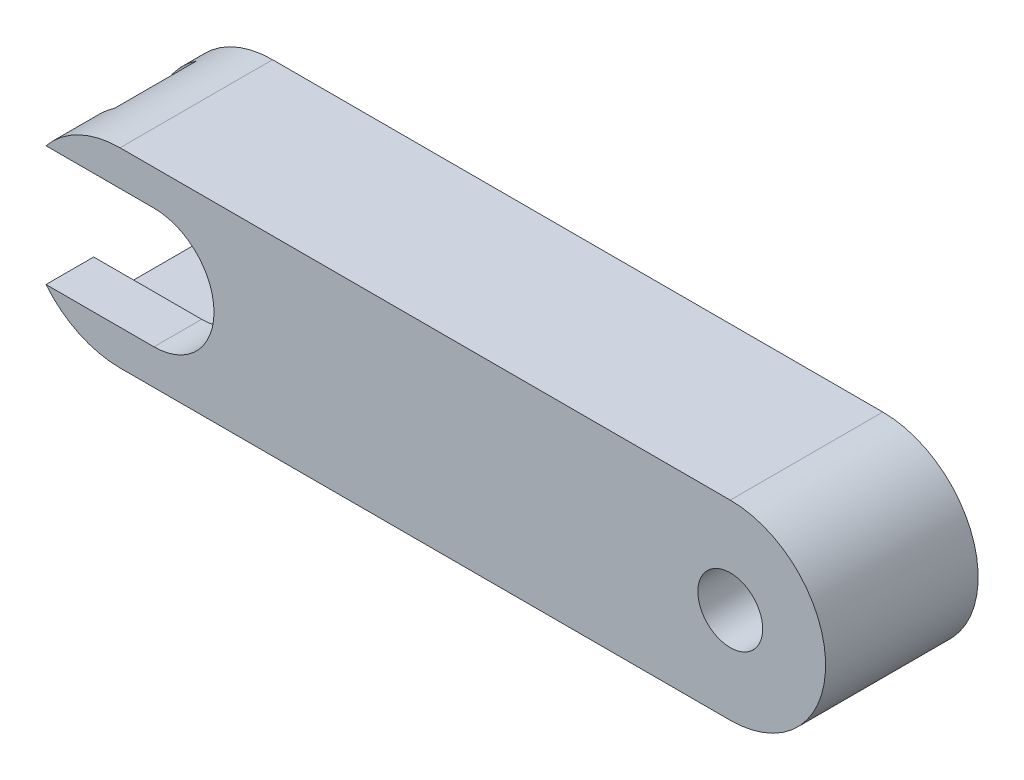
SolidWorks part; units mm, degrees
ref_plane "Front Plane" through (0, 0, 0) normal (0, 0, 1) x (1, 0, 0)
ref_plane "Top Plane" through (0, 0, 0) normal (0, 1, 0) x (1, 0, 0)
ref_plane "Right Plane" through (0, 0, 0) normal (1, 0, 0) x (0, 0, -1)
sketch "Sketch1" plane through (0, 0, 0) normal (0, 0, 1) x (1, 0, 0)
  line L0 (-16, 0) -> (16, 0) construction
  line L1 (-16, 5) -> (16, 5)
  line L2 (-16, -5) -> (16, -5)
  arc A0 (-16, 5) -> (-16, -5) centre (-16, 0) ccw
  arc A1 (16, -5) -> (16, 5) centre (16, 0) ccw
  circle A2 centre (-14.2222, 0) radius 1.7
  circle A3 centre (16, 0) radius 1.7
  point P2 (0, 0)
  point P12 (0, 0)
  dimension "D4" = 3.4
  dimension "D5" = 3.4
  dimension "D1" = 30.2222
  dimension "D2" = 10
  dimension "D3" = 32
extrude "Boss-Extrude1" add sketch "Sketch1" along normal blind 8
sketch "Sketch3" plane through (0, 0, 8) normal (0, 0, 1) x (1, 0, 0)
  line L0 (-20.2222, 0) -> (-14.2222, 0) construction
  line L1 (-20.2222, 3.15) -> (-14.2222, 3.15)
  line L2 (-20.2222, -3.15) -> (-14.2222, -3.15)
  arc A0 (-20.2222, 3.15) -> (-20.2222, -3.15) centre (-20.2222, 0) ccw
  arc A1 (-14.2222, -3.15) -> (-14.2222, 3.15) centre (-14.2222, 0) ccw
  point P2 (-17.2222, 0)
  dimension "D1" = 6.3
  dimension "D2" = 6
extrude "Cut-Extrude1" cut sketch "Sketch3" against normal blind 2.5
sketch "Sketch4" plane through (0, 0, 5.5) normal (0, 0, 1) x (1, 0, 0)
  line L0 (-21, 0) -> (-14.2222, 0) construction
  line L1 (-21, 4.15) -> (-14.2222, 4.15)
  line L2 (-21, -4.15) -> (-14.2222, -4.15)
  arc A0 (-21, 4.15) -> (-21, -4.15) centre (-21, 0) ccw
  arc A1 (-14.2222, -4.15) -> (-14.2222, 4.15) centre (-14.2222, 0) ccw
  circle A3 centre (-14.2222, 0) radius 1.7 construction
  arc A4 (-16, 5) -> (-19.883, 3.15) centre (-16, 0) ccw construction
  point P2 (-17.6111, 0)
  point P8 (0, 0)
  point P11 (0, 0)
  point P15 (0, 0)
  dimension "D1" = 8.3
extrude "Cut-Extrude2" cut sketch "Sketch4" against normal blind 4.3
